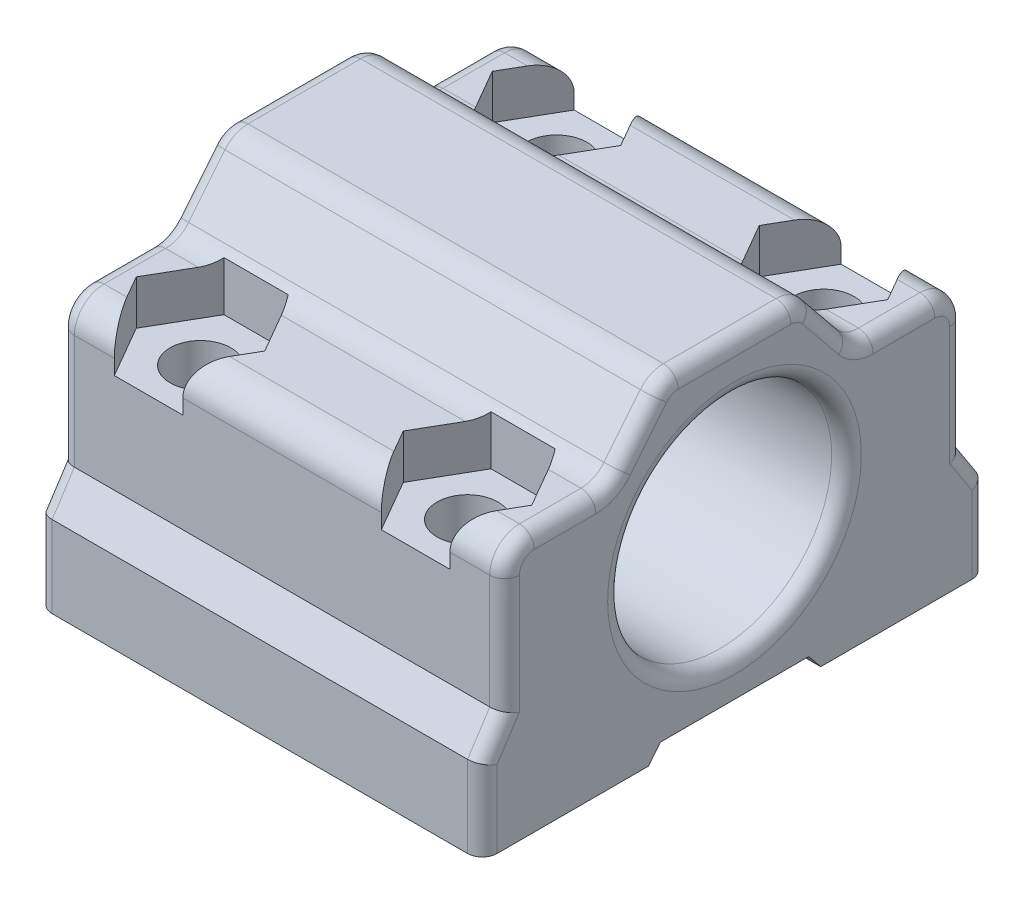
SolidWorks part; units mm, degrees
ref_plane "Front Plane" through (0, 0, 0) normal (0, 0, 1) x (1, 0, 0)
ref_plane "Top Plane" through (0, 0, 0) normal (0, 1, 0) x (1, 0, 0)
ref_plane "Right Plane" through (0, 0, 0) normal (1, 0, 0) x (0, 0, -1)
sketch "Sketch1" plane through (0, 0, 0) normal (0, 1, 0) x (1, 0, 0)
  line L1 (0, 0) -> (30, 0)
  line L2 (0, 0) -> (0, 34)
  line L3 (0, 34) -> (30, 34)
  line L4 (30, 0) -> (30, 34)
  dimension "D1" = 30
  dimension "D2" = 34
extrude "Boss-Extrude1" add sketch "Sketch1" along normal blind 22
sketch "Sketch2" plane through (0, 22, 0) normal (0, 1, 0) x (1, 0, 0)
  line L0 (0, 34) -> (0, 0) construction
  line L1 (6, 29) -> (24, 29) construction
  line L2 (6, 29) -> (6, 5) construction
  line L3 (6, 5) -> (24, 5) construction
  line L4 (24, 29) -> (24, 5) construction
  line L5 (30, 34) -> (0, 34) construction
  circle A0 centre (6, 29) radius 2.05
  circle A1 centre (24, 29) radius 2.05
  circle A2 centre (24, 5) radius 2.05
  circle A3 centre (6, 5) radius 2.05
  point P6 (0, 17)
  point P7 (6, 17)
  point P10 (15, 34)
  point P11 (15, 29)
  dimension "D3" = 4.1
  dimension "D1" = 18
  dimension "D2" = 24
extrude "Cut-Extrude1" cut sketch "Sketch2" against normal blind 22
sketch "Sketch3" plane through (0, 0, 0) normal (-1, 0, 0) x (0, 0, 1)
  line L0 (-34, 22) -> (0, 22) construction
  line L1 (-34, 22) -> (-34, 0) construction
  line L2 (-34, 0) -> (-34, 5.5)
  line L3 (-30.5, 17.5) -> (-26.353, 17.5)
  line L4 (-24.7997, 18.2401) -> (-22.3503, 21.2599)
  line L5 (-20.797, 22) -> (-13.203, 22)
  line L6 (-11.6497, 21.2599) -> (-9.2003, 18.2401)
  line L7 (-7.647, 17.5) -> (-3.5, 17.5)
  line L9 (0, 5.5) -> (0, 0)
  line L10 (0, 0) -> (-11.1889, 0)
  line L11 (-34, 0) -> (0, 0) construction
  line L12 (-11.1889, 0) -> (-12, 1)
  line L13 (-12, 1) -> (-22, 1)
  line L14 (-22, 1) -> (-22.8111, 0)
  line L15 (-22.8111, 0) -> (-34, 0)
  line L16 (-34, 5.5) -> (-32.5, 7.8049)
  line L17 (-32.5, 7.8049) -> (-32.5, 15.5)
  line L18 (0, 5.5) -> (-1.5, 7.8049)
  line L19 (-1.5, 7.8049) -> (-1.5, 15.5)
  circle A0 centre (-17, 11) radius 7.55
  arc A1 (-32.5, 15.5) -> (-30.5, 17.5) centre (-30.5, 15.5) cw
  arc A2 (-1.5, 15.5) -> (-3.5, 17.5) centre (-3.5, 15.5) ccw
  arc A3 (-7.647, 17.5) -> (-9.2003, 18.2401) centre (-7.647, 19.5) cw
  arc A4 (-26.353, 17.5) -> (-24.7997, 18.2401) centre (-26.353, 19.5) ccw
  arc A5 (-11.6497, 21.2599) -> (-13.203, 22) centre (-13.203, 20) ccw
  arc A6 (-20.797, 22) -> (-22.3503, 21.2599) centre (-20.797, 20) ccw
  point P4 (-17, 22)
  point P7 (-34, 11)
  point P17 (-32.5, 17.5)
  point P25 (-17, 1)
  point P27 (-17, 0)
  point P28 (-17, 22)
  point P40 (-25.4, 17.5)
  point P43 (-12.25, 22)
  point P46 (-21.75, 22)
  line M22 (-34, 0) -> (0, 0)
  line M23 (0, 0) -> (0, 22)
  line M24 (0, 22) -> (-34, 22)
  line M25 (-34, 22) -> (-34, 0)
  dimension "D1" = 15.1
  dimension "D10" = 2
  dimension "D11" = 2
  dimension "D2" = 17.5
  dimension "D3" = 1.5
  dimension "D4" = 5.5
  dimension "D5" = 2.75
  dimension "D6" = 9.5
  dimension "D7" = 7.1
  dimension "D8" = 1
  dimension "D9" = 10
extrude "Cut-Extrude2" cut sketch "Sketch3" against normal through all contours A6 L16 L17 A1 L3 A4 L4 M24 M25 | A5 L6 A3 L7 A2 L19 L18 M23 M24 | A0 | L13 L14 L12 M22
sketch "Sketch4" plane through (0, 17.5, 0) normal (0, 1, 0) x (1, 0, 0)
  line L1 (8.1651, 32.75) -> (3.8349, 32.75)
  line L2 (3.8349, 32.75) -> (1.6699, 29)
  line L3 (1.6699, 29) -> (3.8349, 25.25)
  line L4 (3.8349, 25.25) -> (8.1651, 25.25)
  line L5 (8.1651, 25.25) -> (10.3301, 29)
  line L6 (10.3301, 29) -> (8.1651, 32.75)
  line L7 (26.1651, 32.75) -> (21.8349, 32.75)
  line L8 (21.8349, 32.75) -> (19.6699, 29)
  line L9 (19.6699, 29) -> (21.8349, 25.25)
  line L10 (21.8349, 25.25) -> (26.1651, 25.25)
  line L11 (26.1651, 25.25) -> (28.3301, 29)
  line L12 (28.3301, 29) -> (26.1651, 32.75)
  line L13 (21.8349, 1.25) -> (26.1651, 1.25)
  line L14 (26.1651, 1.25) -> (28.3301, 5)
  line L15 (28.3301, 5) -> (26.1651, 8.75)
  line L16 (26.1651, 8.75) -> (21.8349, 8.75)
  line L17 (21.8349, 8.75) -> (19.6699, 5)
  line L18 (19.6699, 5) -> (21.8349, 1.25)
  line L19 (8.1651, 1.25) -> (10.3301, 5)
  line L20 (10.3301, 5) -> (8.1651, 8.75)
  line L21 (8.1651, 8.75) -> (3.8349, 8.75)
  line L22 (3.8349, 8.75) -> (1.6699, 5)
  line L23 (1.6699, 5) -> (3.8349, 1.25)
  line L24 (3.8349, 1.25) -> (8.1651, 1.25)
  circle A0 centre (6, 29) radius 3.75 construction
  circle A1 centre (24, 29) radius 3.75 construction
  circle A2 centre (24, 5) radius 3.75 construction
  circle A3 centre (6, 5) radius 3.75 construction
  arc A4 (7.3973, 3.5) -> (4.6027, 3.5) centre (6, 5) ccw construction
  arc A6 (25.3973, 3.5) -> (22.6027, 3.5) centre (24, 5) ccw construction
  arc A7 (22.6027, 30.5) -> (25.3973, 30.5) centre (24, 29) ccw construction
  arc A8 (4.6027, 30.5) -> (7.3973, 30.5) centre (6, 29) ccw construction
  dimension "D1" = 7.5
extrude "Cut-Extrude3" cut sketch "Sketch4" against normal blind 3 and the other way blind 3
fillet "Fillet1" radius 1 36 edges at (30, 11.6524, -1.5) (30, 16.9142, -2.0858) (30, 17.5, -5.5735) (30, 17.6945, -8.5073) (30, 19.75, -10.425) (30, 21.8055, -12.3427) (30, 11.6524, -32.5) (30, 16.9142, -31.9142) (30, 17.5, -28.4265) (30, 17.6945, -25.4927) (30, 19.75, -23.575) (30, 21.8055, -21.6573) (0, 11.6524, -1.5) (0, 16.9142, -2.0858) (0, 17.5, -5.5735) (0, 17.6945, -8.5073) (0, 19.75, -10.425) (0, 21.8055, -12.3427) (0, 22, -17) (0, 21.8055, -21.6573) (0, 19.75, -23.575) (0, 17.6945, -25.4927) (0, 17.5, -28.4265) (0, 16.9142, -31.9142) (0, 11, -9.45) (30, 11, -9.45) (30, 2.75, 0) (30, 6.6524, -0.75) (30, 6.6524, -33.25) (30, 2.75, -34) (30, 22, -17) (0, 2.75, 0) (0, 6.6524, -0.75) (0, 2.75, -34) (0, 6.6524, -33.25) (0, 11.6524, -32.5)
sketch "Sketch5" plane through (0, 1, 0) normal (0, -1, 0) x (1, 0, 0)
  line L0 (29.5, -22) -> (29.5, -12) construction
  line L1 (29.5, -24) -> (27.5, -24) construction
  line L2 (29.5, -24) -> (29.5, -22) construction
  line L3 (29.5, -22) -> (27.5, -22) construction
  line L4 (27.5, -24) -> (27.5, -22) construction
  line L5 (29.5, -24) -> (27.5, -22) construction
  line L6 (29.5, -22) -> (27.5, -24) construction
  line L7 (2.5, -24) -> (0.5, -24) construction
  line L8 (2.5, -24) -> (2.5, -22) construction
  line L9 (2.5, -22) -> (0.5, -22) construction
  line L10 (0.5, -24) -> (0.5, -22) construction
  line L11 (2.5, -24) -> (0.5, -22) construction
  line L12 (2.5, -22) -> (0.5, -24) construction
  line L13 (2.5, -12) -> (0.5, -12) construction
  line L14 (2.5, -12) -> (2.5, -10) construction
  line L15 (2.5, -10) -> (0.5, -10) construction
  line L16 (0.5, -12) -> (0.5, -10) construction
  line L17 (2.5, -12) -> (0.5, -10) construction
  line L18 (2.5, -10) -> (0.5, -12) construction
  line L19 (29.5, -12) -> (27.5, -12) construction
  line L20 (29.5, -12) -> (29.5, -10) construction
  line L21 (29.5, -10) -> (27.5, -10) construction
  line L22 (27.5, -12) -> (27.5, -10) construction
  line L23 (29.5, -12) -> (27.5, -10) construction
  line L24 (29.5, -10) -> (27.5, -12) construction
  line L25 (2.5, -22) -> (2.5, -12) construction
  line L26 (30, -12) -> (30, -22) construction
  line L27 (27.5, -22) -> (27.5, -12) construction
  line L28 (27.5, -17) -> (2.5, -17) construction
  line L29 (29, -34) -> (1, -34) construction
  circle A0 centre (28.5, -23) radius 1.4
  circle A1 centre (1.5, -23) radius 1.4
  circle A2 centre (1.5, -11) radius 1.4
  circle A3 centre (28.5, -11) radius 1.4
  point P0 (28.5, -23)
  point P5 (1.5, -23)
  point P10 (1.5, -11)
  point P15 (28.5, -11)
  point P22 (30, -17)
  point P23 (29.5, -17)
  point P24 (2.5, -17)
  point P27 (15, -17)
  point P30 (15, -34)
  dimension "D4" = 2.8
  dimension "D1" = 10
  dimension "D2" = 25
  dimension "D3" = 2
